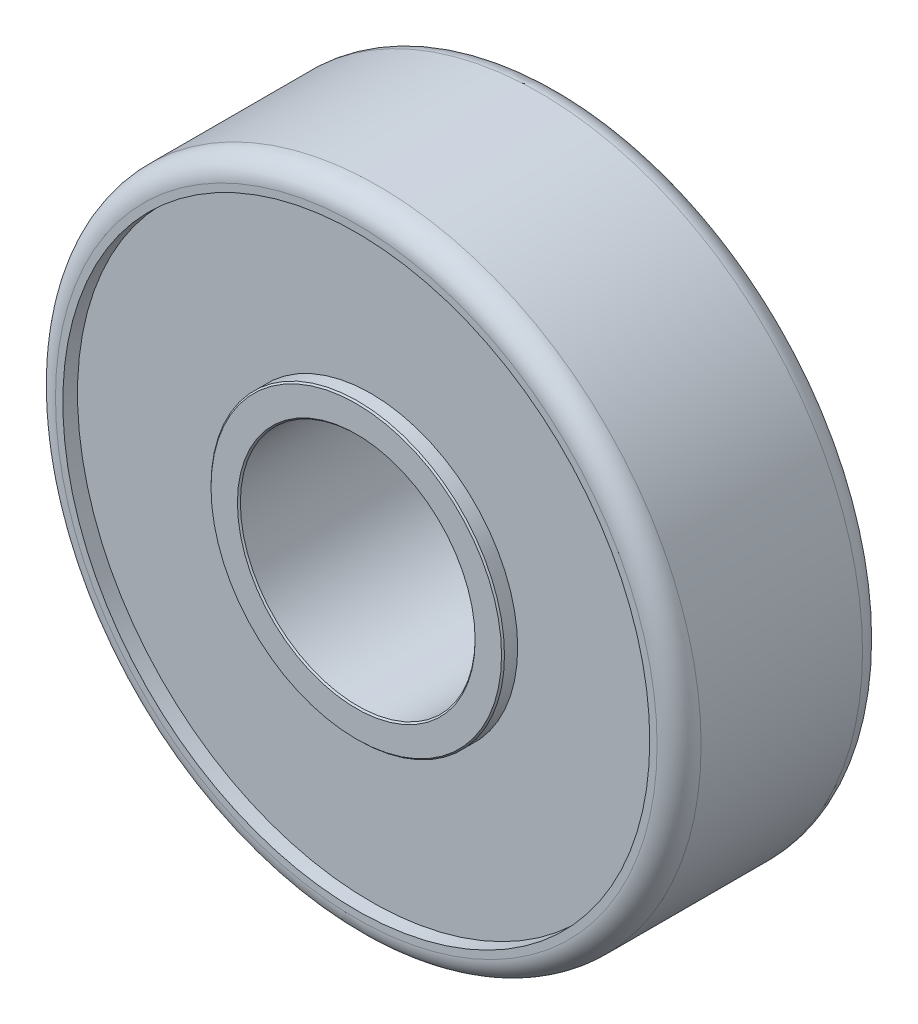
SolidWorks part; units mm, degrees
ref_plane "Plan de face" through (0, 0, 0) normal (0, 0, 1) x (1, 0, 0)
ref_plane "Plan de dessus" through (0, 0, 0) normal (0, 1, 0) x (1, 0, 0)
ref_plane "Plan de droite" through (0, 0, 0) normal (1, 0, 0) x (0, 0, -1)
sketch "Esquisse1" plane through (0, 0, 0) normal (0, 0, 1) x (1, 0, 0)
  circle A0 centre (0, 0) radius 11
  circle A1 centre (0, 0) radius 4
  dimension "D1" = 22
  dimension "D2" = 8
extrude "Boss.-Extru.1" add sketch "Esquisse1" along normal blind 7
sketch "Esquisse2" plane through (0, 0, 7) normal (0, 0, 1) x (1, 0, 0)
  circle A0 centre (0, 0) radius 5
  circle A1 centre (0, 0) radius 10
  circle A2 centre (0, 0) radius 11 construction
  circle A3 centre (0, 0) radius 4 construction
  dimension "D1" = 1
  dimension "D2" = 1
extrude "Enlèv. mat.-Extru.1" cut sketch "Esquisse2" against normal blind 0.5
sketch "Esquisse3" plane through (0, 0, 0) normal (0, 0, -1) x (-1, 0, 0)
  circle A0 centre (0, 0) radius 5
  circle A1 centre (0, 0) radius 10
  circle A2 centre (0, 0) radius 4 construction
  circle A3 centre (0, 0) radius 11 construction
  dimension "D1" = 1
  dimension "D2" = 1
extrude "Enlèv. mat.-Extru.2" cut sketch "Esquisse3" against normal blind 0.5
fillet "Congé1" radius 0.75 2 edges at (11, 0, 0) (11, 0, 7)
chamfer "Chanfrein1" distance 0.05 angle 45 4 edges at (-5, 0, 0) (4, 0, 0) (5, 0, 7) (4, 0, 7)
